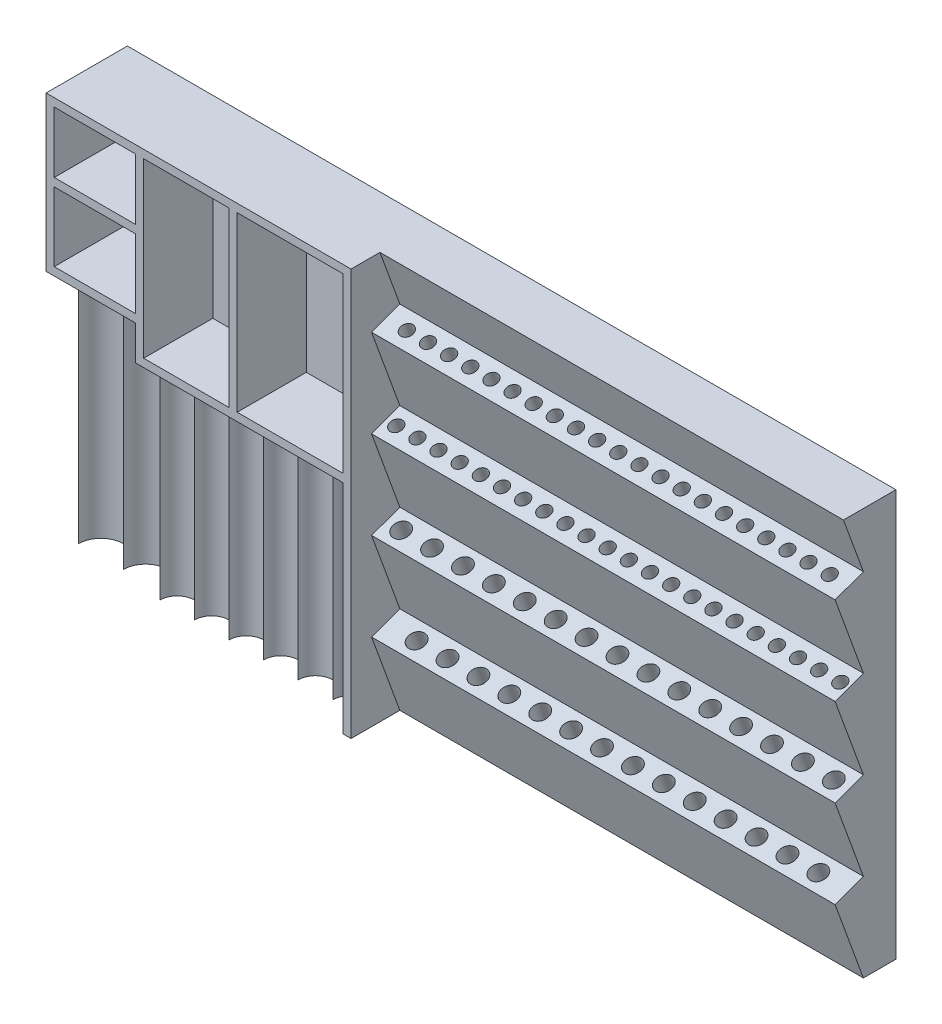
SolidWorks part; units mm, degrees
ref_plane "Front Plane" through (0, 0, 0) normal (0, 0, 1) x (1, 0, 0)
ref_plane "Top Plane" through (0, 0, 0) normal (0, 1, 0) x (1, 0, 0)
ref_plane "Right Plane" through (0, 0, 0) normal (1, 0, 0) x (0, 0, -1)
sketch "Sketch1" plane through (0, 0, 0) normal (0, 0, 1) x (1, 0, 0)
  line L1 (0, 0) -> (240.03, 0)
  line L2 (0, 0) -> (0, 127)
  line L3 (0, 127) -> (240.03, 127)
  line L4 (240.03, 0) -> (240.03, 127)
  dimension "D1" = 240.03
  dimension "D2" = 127
extrude "Boss-Extrude1" add sketch "Sketch1" along normal blind 25.4
sketch "Sketch2" plane through (0, 0, 0) normal (0, -1, 0) x (1, 0, 0)
  line L0 (13.97, 15.24) -> (13.97, 25.4)
  line L1 (0, 25.4) -> (240.03, 25.4) construction
  line L2 (13.97, 25.4) -> (0, 25.4)
  line L3 (0, 25.4) -> (0, 15.24)
  line L4 (0, 25.4) -> (0, 0) construction
  arc A0 (0, 15.24) -> (13.97, 15.24) centre (6.985, 15.24) ccw
  dimension "D1" = 13.97
  dimension "D2" = 10.16
extrude "Cut-Extrude1" cut sketch "Sketch2" against normal blind 78.74
sketch "Sketch3" plane through (0, 0, 0) normal (0, -1, 0) x (1, 0, 0)
  line L0 (27.94, 15.24) -> (27.94, 25.4)
  line L1 (27.94, 25.4) -> (13.97, 25.4)
  line L2 (13.97, 25.4) -> (13.97, 15.24)
  line L3 (13.97, 25.4) -> (240.03, 25.4) construction
  line L4 (13.97, 15.24) -> (13.97, 25.4) construction
  arc A0 (13.97, 15.24) -> (27.94, 15.24) centre (20.955, 15.24) ccw
  dimension "D1" = 6.985
  dimension "D2" = 10.16
extrude "Cut-Extrude2" cut sketch "Sketch3" against normal blind 78.74
sketch "Sketch4" plane through (0, 0, 0) normal (0, -1, 0) x (1, 0, 0)
  line L0 (38.735, 17.78) -> (38.735, 25.4)
  line L1 (27.94, 25.4) -> (240.03, 25.4) construction
  line L2 (38.735, 25.4) -> (27.94, 25.4)
  line L3 (27.94, 25.4) -> (27.94, 17.78)
  line L4 (27.94, 15.24) -> (27.94, 25.4) construction
  arc A0 (27.94, 17.78) -> (38.735, 17.78) centre (33.3375, 17.78) ccw
  dimension "D1" = 10.795
  dimension "D2" = 7.62
extrude "Cut-Extrude3" cut sketch "Sketch4" against normal blind 67.945
pattern_linear "LPattern1" count 6 spacing 10.795 along (1, 0, 0) of "Cut-Extrude3"
sketch "Sketch5" plane through (240.03, 0, 0) normal (1, 0, 0) x (0, 0, -1)
  line L0 (-10.16, 0) -> (-25.4, 0)
  line L1 (-25.4, 0) -> (0, 0) construction
  line L2 (-10.16, 0) -> (-18.9912, 24.2636)
  line L3 (-18.9912, 24.2636) -> (-10.16, 27.4779)
  line L4 (-10.16, 27.4779) -> (-18.9912, 51.7415)
  line L5 (-18.9912, 51.7415) -> (-10.16, 54.9558)
  line L6 (-10.16, 54.9558) -> (-18.9912, 79.2194)
  line L7 (-16.3796, 127) -> (-25.4, 127)
  line L8 (-18.9912, 79.2194) -> (-10.16, 82.4337)
  line L9 (0, 0) -> (0, 127) construction
  line L10 (-25.4, 127) -> (0, 127) construction
  line L11 (-25.4, 0) -> (-25.4, 127)
  line L14 (-10.16, 0) -> (-10.16, 127) construction
  line L15 (-18.9912, 0) -> (-18.9912, 127) construction
  line L16 (-10.16, 82.4337) -> (-18.9912, 106.6973)
  line L17 (-18.9912, 106.6973) -> (-10.16, 109.9117)
  line L18 (-10.16, 109.9117) -> (-16.3796, 127)
  dimension "D1" = 20
  dimension "D2" = 9.398
  dimension "D3" = 10.16
extrude "Cut-Extrude4" cut sketch "Sketch5" against normal blind 144.78
sketch "Sketch6" plane through (0, 51.7926, 18.851) normal (0, 0.9397, 0.342) x (1, 0, 0)
  line L1 (95.25, 4.5497) -> (240.03, 4.5497) construction
  line L6 (95.25, -0.1493) -> (95.25, 9.2487) construction
  line L7 (240.03, -0.1493) -> (240.03, 9.2487) construction
  line L8 (95.25, 19.5684) -> (95.25, -23.8682) construction
  circle A0 centre (100.076, 4.5497) radius 2.6035
  dimension "D1" = 5.207
  dimension "D2" = 4.826
extrude "Cut-Extrude5" cut sketch "Sketch6" against normal blind 25.4
pattern_linear "LPattern2" count 15 spacing 9.652 along (1, 0, 0) of "Cut-Extrude5"
sketch "Sketch7" plane through (0, 27.529, 10.0197) normal (0, 0.9397, 0.342) x (1, 0, 0)
  line L0 (95.25, -4.8483) -> (240.03, -4.8483) construction
  line L1 (95.25, -9.5473) -> (95.25, -0.1493) construction
  line L2 (240.03, -9.5473) -> (240.03, -0.1493) construction
  circle A0 centre (104.902, -4.8483) radius 2.6035
  dimension "D1" = 5.207
  dimension "D2" = 9.652
extrude "Cut-Extrude6" cut sketch "Sketch7" against normal blind 25.4
pattern_linear "LPattern3" count 14 spacing 9.652 along (1, 0, 0) of "Cut-Extrude6"
sketch "Sketch8" plane through (0, 76.0562, 27.6822) normal (0, 0.9397, 0.342) x (1, 0, 0)
  line L0 (95.25, 13.9477) -> (240.03, 13.9477) construction
  line L1 (95.25, 9.2487) -> (95.25, 18.6467) construction
  line L2 (240.03, 9.2487) -> (240.03, 18.6467) construction
  circle A0 centre (98.552, 13.9477) radius 1.9685
  dimension "D2" = 3.937
  dimension "D1" = 3.302
extrude "Cut-Extrude7" cut sketch "Sketch8" against normal blind 19.05
pattern_linear "LPattern4" count 22 spacing 6.604 along (1, 0, 0) of "Cut-Extrude7"
sketch "Sketch9" plane through (0, 100.3198, 36.5134) normal (0, 0.9397, 0.342) x (1, 0, 0)
  line L0 (95.25, 23.3457) -> (240.03, 23.3457) construction
  line L1 (95.25, 18.6467) -> (95.25, 28.0447) construction
  line L2 (240.03, 18.6467) -> (240.03, 28.0447) construction
  line L3 (95.25, 28.0447) -> (95.25, 19.5684) construction
  circle A0 centre (101.854, 23.3457) radius 1.9685
  dimension "D1" = 3.937
  dimension "D2" = 6.604
extrude "Cut-Extrude8" cut sketch "Sketch9" against normal blind 19.05
pattern_linear "LPattern5" count 21 spacing 6.604 along (1, 0, 0) of "Cut-Extrude8"
sketch "Sketch10" plane through (0, 0, 25.4) normal (0, 0, 1) x (1, 0, 0)
  line L0 (95.25, 127) -> (95.25, 0) construction
  line L1 (92.71, 70.485) -> (59.69, 70.485)
  line L2 (92.71, 70.485) -> (92.71, 124.46)
  line L3 (92.71, 124.46) -> (59.69, 124.46)
  line L4 (59.69, 70.485) -> (59.69, 124.46)
  line L5 (92.71, 67.945) -> (27.94, 67.945) construction
  line L6 (27.94, 78.74) -> (27.94, 67.945) construction
  line L7 (95.25, 127) -> (0, 127) construction
  dimension "D1" = 2.54
  dimension "D2" = 2.54
  dimension "D3" = 31.75
  dimension "D4" = 2.54
extrude "Cut-Extrude9" cut sketch "Sketch10" against normal blind 21.59
sketch "Sketch11" plane through (0, 0, 25.4) normal (0, 0, 1) x (1, 0, 0)
  line L0 (92.71, 67.945) -> (27.94, 67.945) construction
  line L1 (57.15, 124.46) -> (30.48, 124.46)
  line L2 (57.15, 124.46) -> (57.15, 70.485)
  line L3 (57.15, 70.485) -> (30.48, 70.485)
  line L4 (30.48, 124.46) -> (30.48, 70.485)
  line L5 (59.69, 124.46) -> (59.69, 70.485) construction
  line L6 (27.94, 78.74) -> (27.94, 0) construction
  line L7 (95.25, 127) -> (0, 127) construction
  dimension "D1" = 2.54
  dimension "D2" = 2.54
  dimension "D3" = 2.54
  dimension "D4" = 2.54
extrude "Cut-Extrude10" cut sketch "Sketch11" against normal blind 21.59
sketch "Sketch12" plane through (0, 0, 25.4) normal (0, 0, 1) x (1, 0, 0)
  line L0 (27.94, 78.74) -> (0, 78.74) construction
  line L1 (2.54, 81.28) -> (27.94, 81.28)
  line L2 (2.54, 81.28) -> (2.54, 102.87)
  line L3 (2.54, 102.87) -> (27.94, 102.87)
  line L4 (27.94, 81.28) -> (27.94, 102.87)
  line L5 (30.48, 124.46) -> (30.48, 70.485) construction
  line L6 (0, 127) -> (0, 78.74) construction
  dimension "D1" = 2.54
  dimension "D2" = 2.54
  dimension "D3" = 2.54
  dimension "D4" = 21.59
extrude "Cut-Extrude11" cut sketch "Sketch12" against normal blind 21.59
sketch "Sketch13" plane through (0, 0, 25.4) normal (0, 0, 1) x (1, 0, 0)
  line L0 (2.54, 102.87) -> (2.54, 81.28) construction
  line L1 (2.54, 124.46) -> (27.94, 124.46)
  line L2 (2.54, 124.46) -> (2.54, 105.41)
  line L3 (2.54, 105.41) -> (27.94, 105.41)
  line L4 (27.94, 124.46) -> (27.94, 105.41)
  line L5 (27.94, 81.28) -> (27.94, 102.87) construction
  line L6 (57.15, 124.46) -> (30.48, 124.46) construction
  line L7 (27.94, 102.87) -> (2.54, 102.87) construction
  dimension "D1" = 2.54
extrude "Cut-Extrude12" cut sketch "Sketch13" against normal blind 21.59
